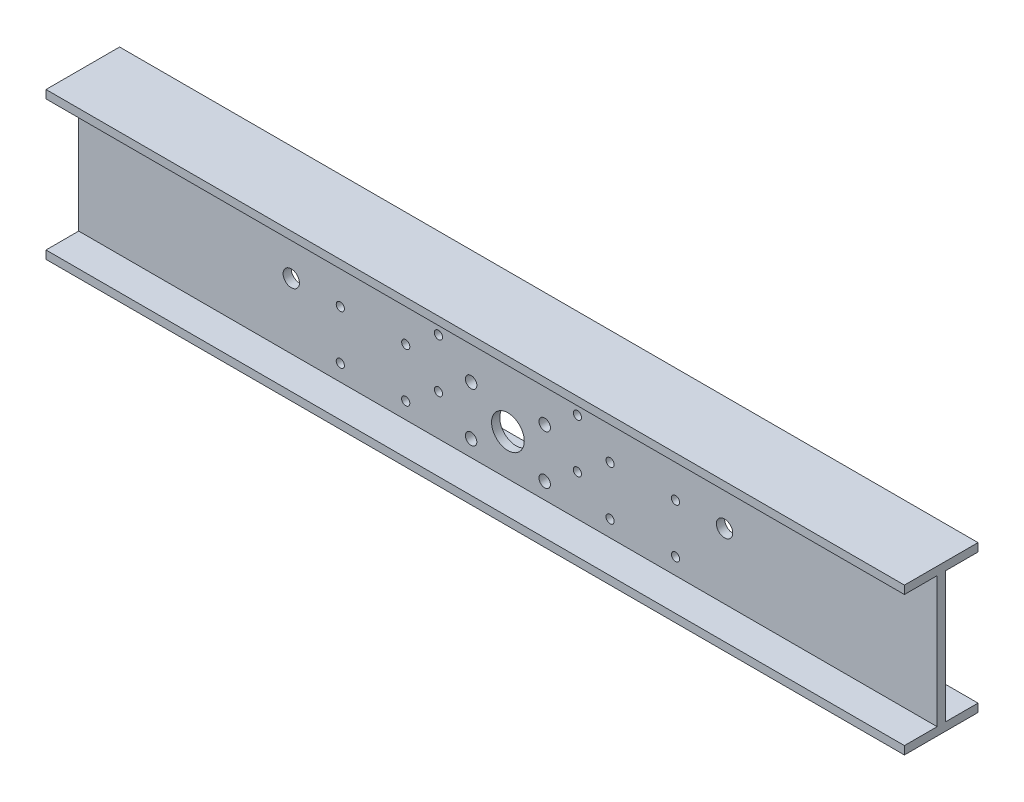
SolidWorks part; units mm, degrees
ref_plane "Plan de face" through (0, 0, 0) normal (0, 0, 1) x (1, 0, 0)
ref_plane "Plan de dessus" through (0, 0, 0) normal (0, 1, 0) x (1, 0, 0)
ref_plane "Plan de droite" through (0, 0, 0) normal (1, 0, 0) x (0, 0, -1)
sketch "Esquisse1" plane through (0, 0, 0) normal (0, 0, 1) x (1, 0, 0)
  line L1 (0, 0) -> (105, 0)
  line L2 (0, 0) -> (0, 18)
  line L3 (0, 18) -> (105, 18)
  line L6 (105, 0) -> (105, 18)
  circle A0 centre (26, 9) radius 1
  circle A1 centre (32, 15) radius 0.5
  circle A2 centre (32, 9) radius 0.5
  circle A3 centre (32, 3) radius 0.5
  circle A4 centre (40, 15) radius 0.5
  circle A5 centre (40, 9) radius 0.5
  circle A6 centre (40, 3) radius 0.5
  circle A7 centre (44, 6) radius 0.5
  circle A8 centre (44, 12) radius 0.5
  circle A9 centre (48, 3) radius 0.7
  circle A10 centre (48, 9) radius 0.7
  circle A11 centre (48, 15) radius 0.5
  circle A12 centre (52.5, 6) radius 2
  circle A13 centre (57, 15) radius 0.5
  circle A14 centre (57, 9) radius 0.7
  circle A15 centre (57, 3) radius 0.7
  circle A16 centre (61, 12) radius 0.5
  circle A17 centre (61, 6) radius 0.5
  circle A18 centre (65, 3) radius 0.5
  circle A19 centre (65, 9) radius 0.5
  circle A20 centre (65, 15) radius 0.5
  circle A21 centre (73, 3) radius 0.5
  circle A22 centre (73, 9) radius 0.5
  circle A23 centre (73, 15) radius 0.5
  circle A24 centre (79, 9) radius 1
  point P60 (52.5, 17)
  point P63 (52.5, 1)
extrude "Boss.-Extru.5" add sketch "Esquisse1" along normal blind 0.5
sketch "Esquisse11" plane through (0, 0, 0.5) normal (0, 0, 1) x (1, 0, 0)
  line L0 (105, 0) -> (105, 18) construction
  line L1 (0, 0) -> (105, 0)
  line L2 (0, 0) -> (0, 1)
  line L3 (0, 1) -> (105, 1)
  line L4 (105, 0) -> (105, 1)
  line L6 (0, 18) -> (105, 18)
  line L7 (0, 18) -> (0, 17)
  line L8 (0, 17) -> (105, 17)
  line L9 (105, 18) -> (105, 17)
extrude "Boss.-Extru.7" add sketch "Esquisse11" along normal blind 4
mirror "Symétrie1" about plane through (0, 0, 0) normal (0, 0, -1) of "Boss.-Extru.5", "Boss.-Extru.7"
sketch "Esquisse12" plane through (0, 18, 0) normal (0, 1, 0) x (1, 0, 0)
  line L0 (105, -4.5) -> (0, -4.5) construction
  point P0 (52.5, -4.5)
  point P1 (52.5, -4.5)
  point P5 (0, 0)
